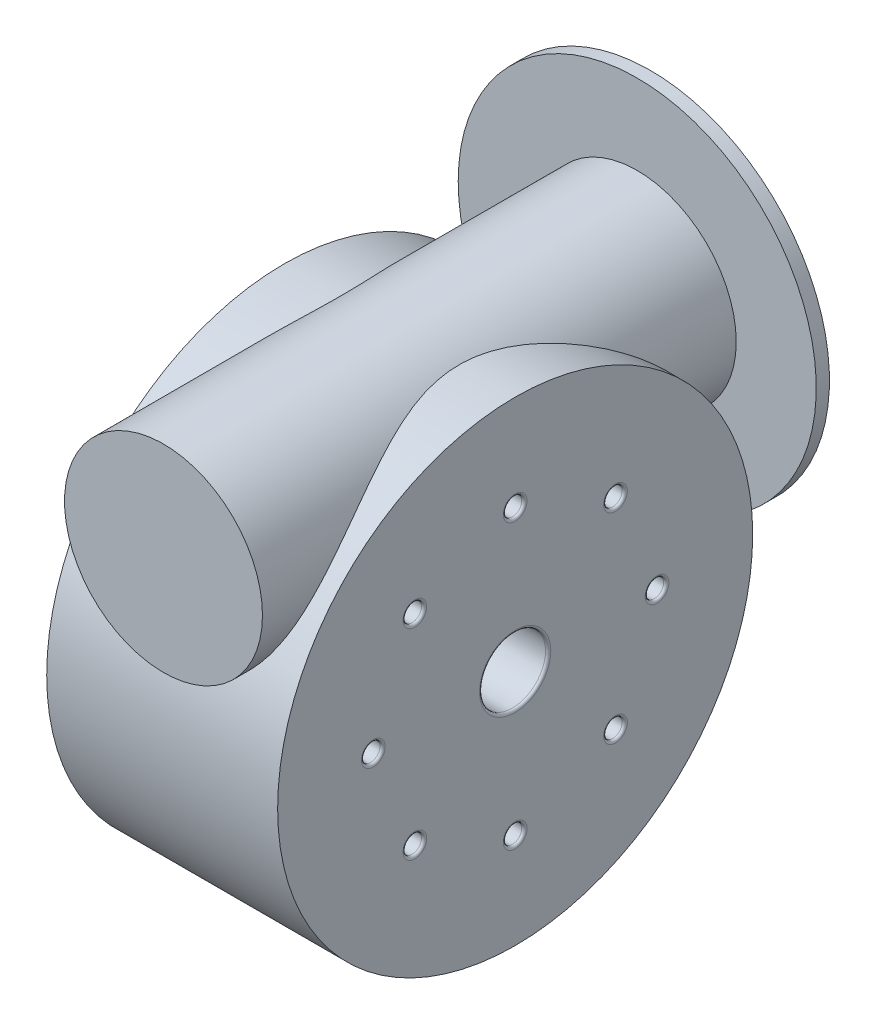
SolidWorks part; units mm, degrees
material "Malleable Cast Iron"
ref_plane "Front Plane" through (0, 0, 0) normal (0, 0, 1) x (1, 0, 0)
ref_plane "Top Plane" through (0, 0, 0) normal (0, 1, 0) x (1, 0, 0)
ref_plane "Right Plane" through (0, 0, 0) normal (1, 0, 0) x (0, 0, -1)
sketch "Sketch1" plane through (0, 0, 0) normal (1, 0, 0) x (0, 0, -1)
  circle A0 centre (0, 0) radius 180
  dimension "D1" = 360
extrude "Boss-Extrude1" add sketch "Sketch1" along normal mid plane 175
sketch "Sketch2" plane through (-87.5, 0, 0) normal (-1, 0, 0) x (0, 0, 1)
  circle A0 centre (0, 0) radius 107.5 construction
  circle A1 centre (0, 107.5) radius 7
  dimension "D1" = 215
  dimension "D2" = 14
extrude "Cut-Extrude1" cut sketch "Sketch2" against normal through all
fillet "Fillet1" radius 2 2 edges at (-87.5, 107.5, 7) (87.5, 107.5, 7)
pattern_circular "CirPattern1" count 8 over 360 about axis through (0, 0, 0) along (1, 0, 0) of "Cut-Extrude1", "Fillet1"
sketch "Sketch3" plane through (87.5, 0, 0) normal (1, 0, 0) x (0, 0, -1)
  circle A0 centre (0, 0) radius 25
  dimension "D1" = 50
extrude "Cut-Extrude2" cut sketch "Sketch3" against normal blind 314.5333
fillet "Fillet2" radius 2 2 edges at (87.5, 0, -25) (-87.5, 0, -25)
sketch "Sketch5" plane through (0, 0, 0) normal (0, 0, 1) x (1, 0, 0)
  circle A0 centre (0, 120) radius 75
  dimension "D1" = 150
  dimension "D2" = 120
extrude "Boss-Extrude2" add sketch "Sketch5" along normal blind 179 and the other way blind 190
sketch "Sketch6" plane through (0, 0, -190) normal (0, 0, -1) x (-1, 0, 0)
  circle A0 centre (0, 120) radius 135.6682
  dimension "D1" = 271.3364
extrude "Boss-Extrude3" add sketch "Sketch6" against normal blind 10 separate body
